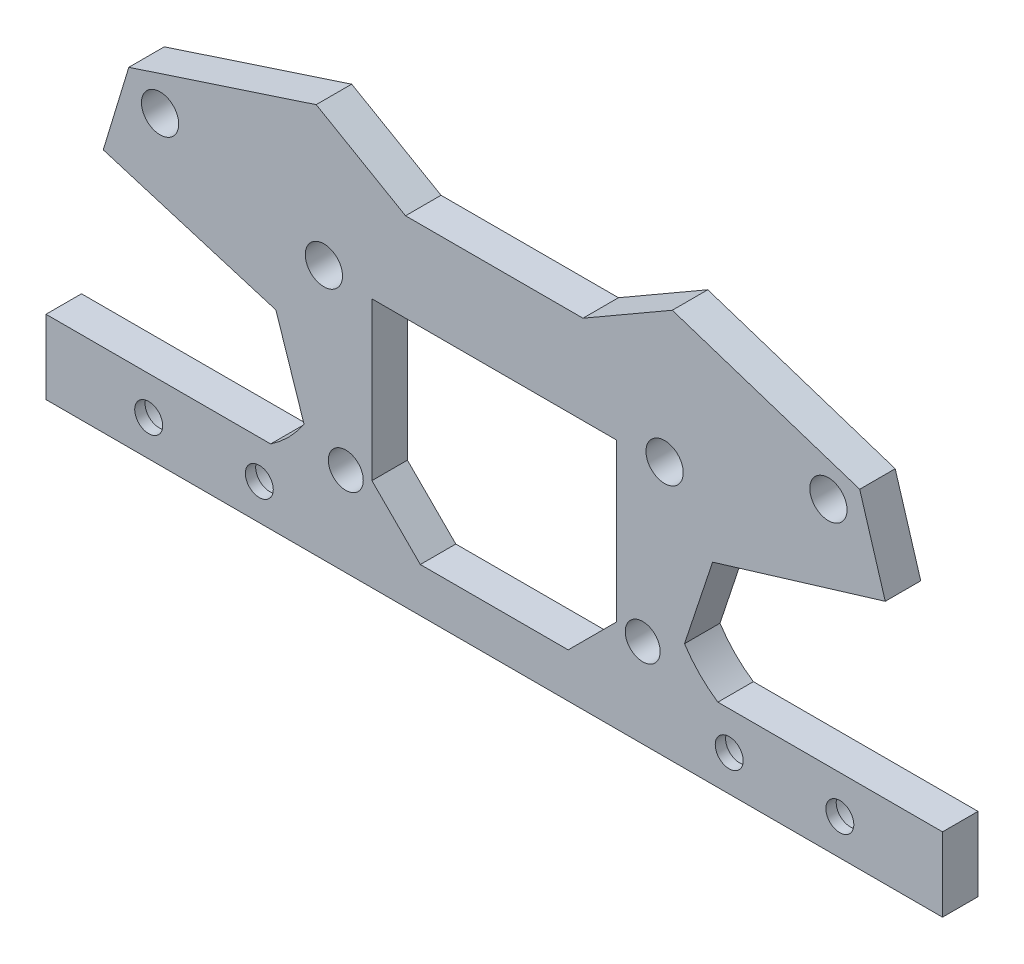
SolidWorks part; units mm, degrees
ref_plane "Front Plane" through (0, 0, 0) normal (0, 0, 1) x (1, 0, 0)
ref_plane "Top Plane" through (0, 0, 0) normal (0, 1, 0) x (1, 0, 0)
ref_plane "Right Plane" through (0, 0, 0) normal (1, 0, 0) x (0, 0, -1)
sketch "Sketch1" plane through (0, 0, 0) normal (0, 0, 1) x (1, 0, 0)
  line L0 (63.1705, -199.162) -> (55.4982, -203.5916)
  line L1 (55.4982, -203.5916) -> (40.2582, -203.5916)
  line L2 (47.8782, -203.5916) -> (47.8782, -232.7833)
  line L3 (58.3862, -211.2116) -> (58.3862, -232.7066)
  line L4 (58.3862, -232.7066) -> (86.3782, -232.7066)
  line L5 (86.3782, -228.0816) -> (86.3782, -237.3316) construction
  line L6 (86.3782, -232.7066) -> (86.3782, -226.3566)
  line L7 (86.3782, -226.3566) -> (67.0838, -226.3566)
  line L8 (58.3862, -211.2116) -> (47.8782, -211.2116)
  line L9 (63.1429, -200.4768) -> (67.4731, -197.9768) construction
  line L10 (57.8782, -218.8316) -> (37.8782, -218.8316) construction
  line L11 (57.8782, -225.8316) -> (57.8782, -218.8316) construction
  line L12 (62.51, -210.7817) -> (76.5795, -206.5137) construction
  line L13 (81.4611, -211.6687) -> (62.6013, -217.3897)
  line L14 (63.1705, -199.162) -> (79.2654, -204.4304)
  line L15 (79.2654, -204.4304) -> (81.4611, -211.6687)
  line L16 (47.8782, -212.3788) -> (47.8782, -200.1352) construction
  line L17 (66.6318, -216.1671) -> (64.2183, -223.4426)
  circle A0 centre (62.51, -210.7817) radius 1.6 construction
  circle A1 centre (62.51, -210.7817) radius 1.6
  circle A2 centre (33.2464, -210.7817) radius 1.6 construction
  circle A3 centre (33.2464, -210.7817) radius 1.6
  circle A4 centre (76.5795, -206.5137) radius 1.6 construction
  circle A5 centre (76.5795, -206.5137) radius 1.6
  circle A6 centre (19.1769, -206.5137) radius 1.6 construction
  circle A7 centre (19.1769, -206.5137) radius 1.6
  circle A8 centre (35.1282, -225.0816) radius 1.5 construction
  circle A9 centre (35.1282, -225.0816) radius 1.5
  circle A10 centre (60.6282, -225.0816) radius 1.5 construction
  circle A11 centre (60.6282, -225.0816) radius 1.5
  arc A12 (62.6282, -218.8316) -> (72.7474, -228.0816) centre (72.7474, -217.9216) ccw construction
  arc A13 (62.6282, -218.8316) -> (67.0838, -226.3566) centre (72.7474, -217.9216) ccw
  arc A14 (62.6282, -218.8316) -> (62.6013, -217.3897) centre (72.7474, -217.9216) cw
  spline S0 degree 3 poles (16.9982, -229.6316) (16.9982, -232.0316) (19.3982, -232.0316) (19.3982, -229.6316) (19.3982, -227.2316) (16.9982, -227.2316) (16.9982, -229.6316) (16.9982, -232.0316) (19.3982, -232.0316) knots -0.5 0 0 0 0.5 0.5 0.5 1 1 1 1.5 1.5 1.5 weights 1 0.333333 0.333333 1 0.333333 0.333333 1 0.333333 0.333333 only from (16.9982, -229.6316) to (16.9982, -229.6316) construction
  spline S1 degree 3 poles (26.4982, -229.6316) (26.4982, -232.0316) (28.8982, -232.0316) (28.8982, -229.6316) (28.8982, -227.2316) (26.4982, -227.2316) (26.4982, -229.6316) (26.4982, -232.0316) (28.8982, -232.0316) knots -0.5 0 0 0 0.5 0.5 0.5 1 1 1 1.5 1.5 1.5 weights 1 0.333333 0.333333 1 0.333333 0.333333 1 0.333333 0.333333 only from (26.4982, -229.6316) to (26.4982, -229.6316) construction
  spline S2 degree 3 poles (78.7582, -229.6316) (78.7582, -227.2316) (76.3582, -227.2316) (76.3582, -229.6316) (76.3582, -232.0316) (78.7582, -232.0316) (78.7582, -229.6316) (78.7582, -227.2316) (76.3582, -227.2316) knots -0.5 0 0 0 0.5 0.5 0.5 1 1 1 1.5 1.5 1.5 weights 1 0.333333 0.333333 1 0.333333 0.333333 1 0.333333 0.333333 only from (78.7582, -229.6316) to (78.7582, -229.6316) construction
  spline S3 degree 3 poles (69.2582, -229.6316) (69.2582, -227.2316) (66.8582, -227.2316) (66.8582, -229.6316) (66.8582, -232.0316) (69.2582, -232.0316) (69.2582, -229.6316) (69.2582, -227.2316) (66.8582, -227.2316) knots -0.5 0 0 0 0.5 0.5 0.5 1 1 1 1.5 1.5 1.5 weights 1 0.333333 0.333333 1 0.333333 0.333333 1 0.333333 0.333333 only from (69.2582, -229.6316) to (69.2582, -229.6316) construction
  spline S4 degree 3 poles (16.9982, -229.6316) (16.9982, -232.0316) (19.3982, -232.0316) (19.3982, -229.6316) (19.3982, -227.2316) (16.9982, -227.2316) (16.9982, -229.6316) (16.9982, -232.0316) (19.3982, -232.0316) knots -0.5 0 0 0 0.5 0.5 0.5 1 1 1 1.5 1.5 1.5 weights 1 0.333333 0.333333 1 0.333333 0.333333 1 0.333333 0.333333 only from (16.9982, -229.6316) to (16.9982, -229.6316)
  spline S5 degree 3 poles (26.4982, -229.6316) (26.4982, -232.0316) (28.8982, -232.0316) (28.8982, -229.6316) (28.8982, -227.2316) (26.4982, -227.2316) (26.4982, -229.6316) (26.4982, -232.0316) (28.8982, -232.0316) knots -0.5 0 0 0 0.5 0.5 0.5 1 1 1 1.5 1.5 1.5 weights 1 0.333333 0.333333 1 0.333333 0.333333 1 0.333333 0.333333 only from (26.4982, -229.6316) to (26.4982, -229.6316)
  spline S6 degree 3 poles (78.7582, -229.6316) (78.7582, -227.2316) (76.3582, -227.2316) (76.3582, -229.6316) (76.3582, -232.0316) (78.7582, -232.0316) (78.7582, -229.6316) (78.7582, -227.2316) (76.3582, -227.2316) knots -0.5 0 0 0 0.5 0.5 0.5 1 1 1 1.5 1.5 1.5 weights 1 0.333333 0.333333 1 0.333333 0.333333 1 0.333333 0.333333 only from (78.7582, -229.6316) to (78.7582, -229.6316)
  spline S7 degree 3 poles (69.2582, -229.6316) (69.2582, -227.2316) (66.8582, -227.2316) (66.8582, -229.6316) (66.8582, -232.0316) (69.2582, -232.0316) (69.2582, -229.6316) (69.2582, -227.2316) (66.8582, -227.2316) knots -0.5 0 0 0 0.5 0.5 0.5 1 1 1 1.5 1.5 1.5 weights 1 0.333333 0.333333 1 0.333333 0.333333 1 0.333333 0.333333 only from (69.2582, -229.6316) to (69.2582, -229.6316)
  point P46 (64.2183, -223.4426)
  dimension "D1" = 7.62
  dimension "D2" = 7.62
  dimension "D3" = 0.508
  dimension "D4" = 6.35
  dimension "D5" = 6.35
  dimension "D6" = 55
  dimension "D7" = 3.175
  dimension "D8" = 8.8592
  dimension "D9" = 15.24
extrude "Boss-Extrude1" add sketch "Sketch1" along normal blind 3.048
sketch "Sketch2" plane through (0, 0, 0) normal (0, 0, -1) x (-1, 0, 0)
  circle A0 centre (-77.5582, -229.6316) radius 2
  circle A1 centre (-68.0582, -229.6316) radius 2
  dimension "D1" = 4
extrude "Cut-Extrude1" cut sketch "Sketch2" against normal blind 2.159
mirror "Mirror1" about plane through (47.8782, 0, 3.048) normal (1, 0, 0) of bodies 102
sketch "Sketch3" plane through (0, 0, 3.048) normal (0, 0, 1) x (1, 0, 0)
  line L0 (37.3702, -224.7386) -> (41.5282, -228.8966)
  line L1 (37.3702, -211.2116) -> (37.3702, -232.7066) construction
  line L2 (41.5282, -228.8966) -> (54.2282, -228.8966)
  line L3 (54.2282, -228.8966) -> (58.3862, -224.7386)
  line L4 (58.3862, -211.2116) -> (58.3862, -232.7066) construction
  line L5 (37.3702, -232.7066) -> (58.3862, -232.7066)
  line L7 (58.3862, -211.2116) -> (58.3862, -232.7066)
  line L8 (37.3702, -211.2116) -> (37.3702, -232.7066)
  point P10 (47.8782, -232.7066)
  point P11 (47.8782, -228.8966)
  line M17 (37.3702, -232.7066) -> (37.3702, -211.2116)
  line M19 (58.3862, -211.2116) -> (58.3862, -232.7066)
  dimension "D1" = 3.81
  dimension "D2" = 45
  dimension "D3" = 12.7
extrude "Boss-Extrude2" add sketch "Sketch3" against normal up to surface (3.048 mm away) contours L5 L3 L2 L0 M17 M19 up to face at (75.5582, -229.6316, 0)
